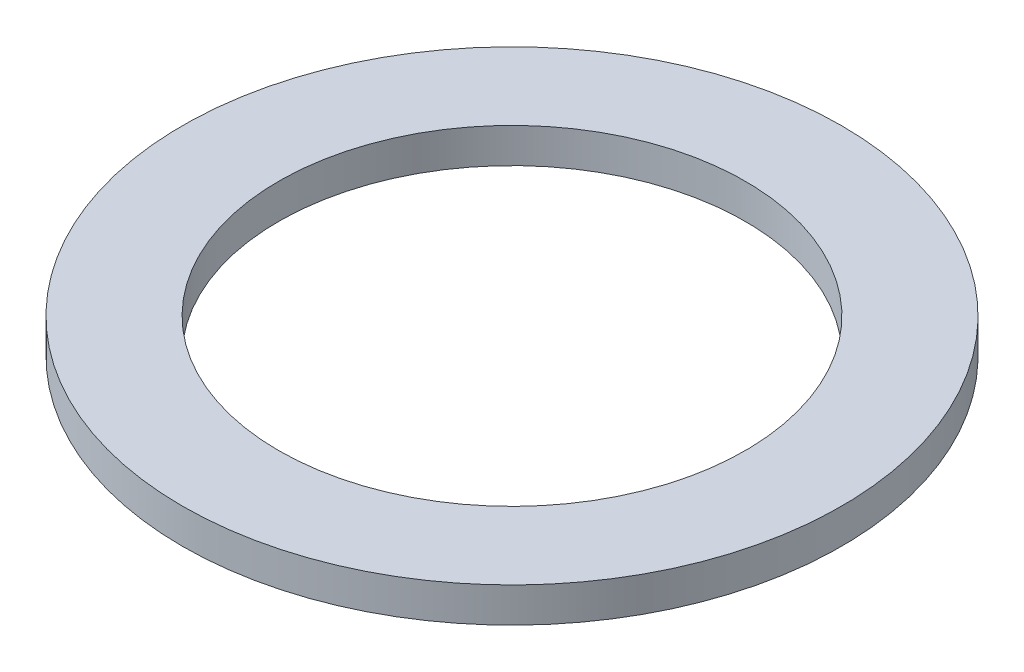
SolidWorks part; units mm, degrees
ref_plane "Front Plane" through (0, 0, 0) normal (0, 0, 1) x (1, 0, 0)
ref_plane "Top Plane" through (0, 0, 0) normal (0, 1, 0) x (1, 0, 0)
ref_plane "Right Plane" through (0, 0, 0) normal (1, 0, 0) x (0, 0, -1)
sketch "Sketch1" plane through (0, 0, 0) normal (0, 1, 0) x (1, 0, 0)
  circle A0 centre (0, 0) radius 22
  circle A1 centre (0, 0) radius 15.575
extrude "Boss-Extrude1" add sketch "Sketch1" against normal blind 2.325
